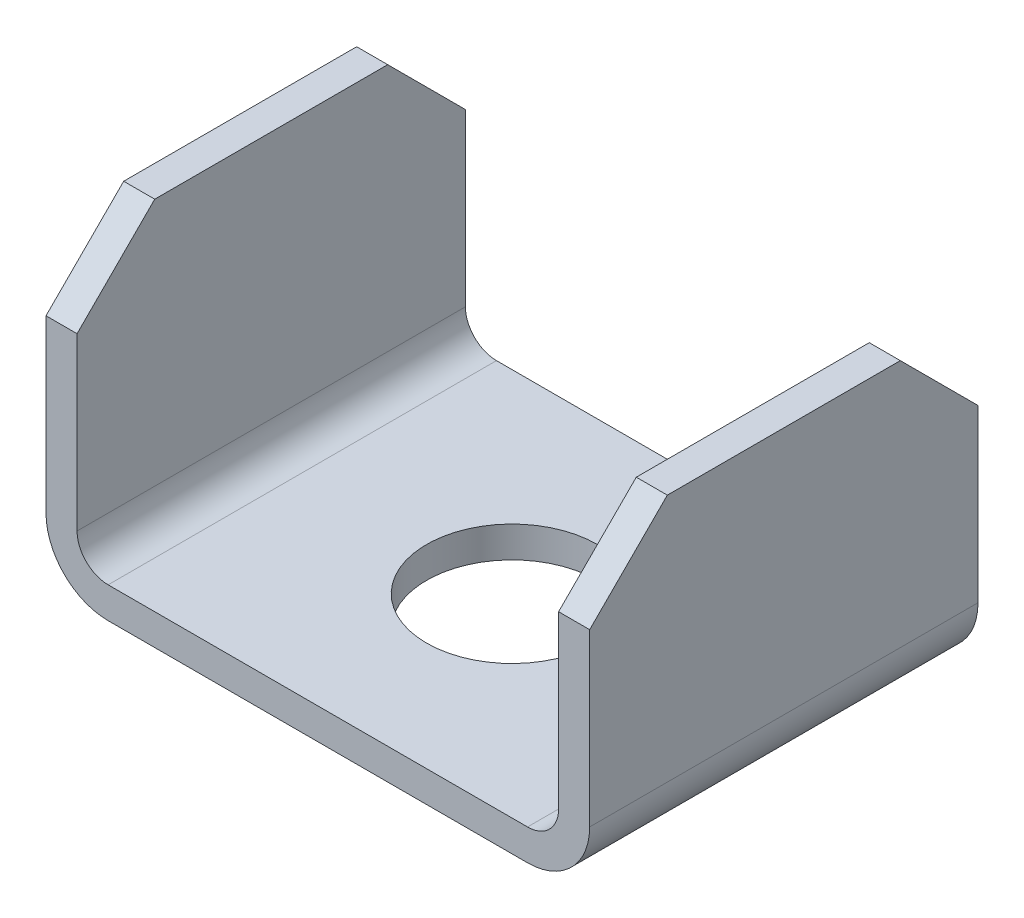
SolidWorks part; units mm, degrees
ref_plane "Front Plane" through (0, 0, 0) normal (0, 0, 1) x (1, 0, 0)
ref_plane "Top Plane" through (0, 0, 0) normal (0, 1, 0) x (1, 0, 0)
ref_plane "Right Plane" through (0, 0, 0) normal (1, 0, 0) x (0, 0, -1)
sketch "Sketch1" plane through (0, 0, 0) normal (0, 0, 1) x (1, 0, 0)
  line L1 (-35, 20) -> (35, 20)
  line L2 (-35, 20) -> (-35, -20)
  line L3 (-35, -20) -> (35, -20)
  line L4 (35, 20) -> (35, -20)
  line L5 (-35, 20) -> (35, -20) construction
  line L6 (-35, -20) -> (35, 20) construction
  point P0 (0, 0)
  dimension "D1" = 70
  dimension "D2" = 40
extrude "Boss-Extrude1" add sketch "Sketch1" along normal mid plane 50
fillet "Fillet1" radius 8 2 edges at (35, -20, 0) (-35, -20, 0)
shell "Shell1" thickness 4
chamfer "Chamfer1" distance 10 angle 45 4 edges at (33, 20, 25) (-33, 20, 25) (-33, 20, -25) (33, 20, -25)
sketch "Sketch2" plane through (0, -16, 0) normal (0, 1, 0) x (1, 0, 0)
  circle A0 centre (0, 0) radius 11
  dimension "D1" = 22
extrude "Cut-Extrude1" cut sketch "Sketch2" against normal up to next
